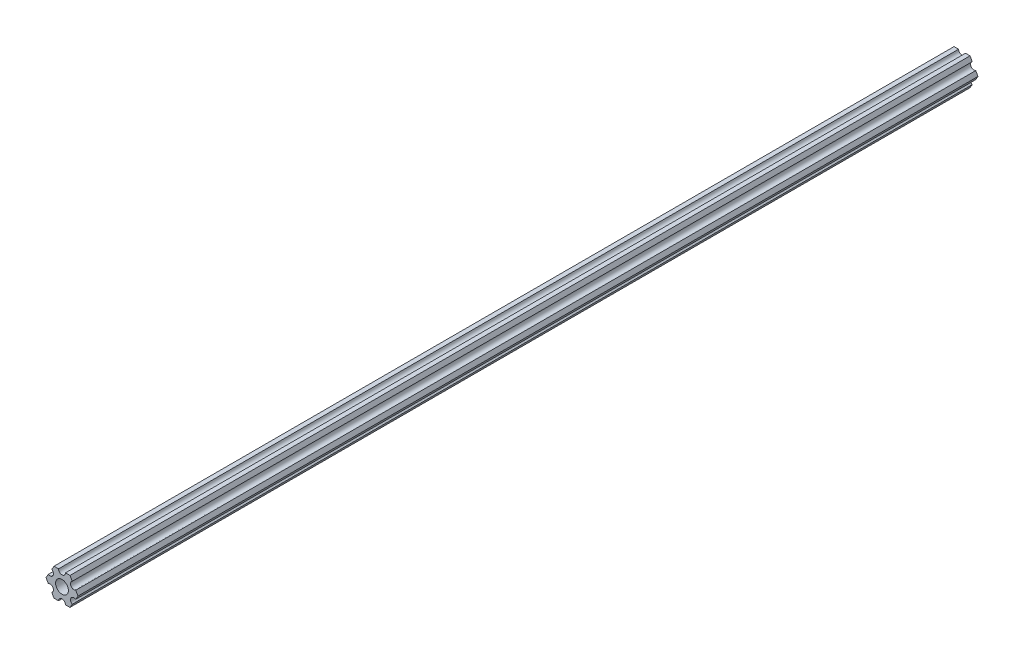
SolidWorks part; units mm, degrees
ref_plane "Front Plane" through (0, 0, 0) normal (0, 0, 1) x (1, 0, 0)
ref_plane "Top Plane" through (0, 0, 0) normal (0, 1, 0) x (1, 0, 0)
ref_plane "Right Plane" through (0, 0, 0) normal (1, 0, 0) x (0, 0, -1)
sketch "Sketch1" plane through (0, 0, 0) normal (0, 0, 1) x (1, 0, 0)
  line L0 (-1.5875, 6.35) -> (-3.6662, 6.35)
  line L1 (7.3323, 0) -> (6.293, 1.8002)
  line L2 (3.6662, 6.35) -> (1.5875, 6.35)
  line L3 (-3.6662, 6.35) -> (-4.7055, 4.5498)
  line L4 (-7.3323, 0) -> (-6.293, -1.8002)
  line L5 (-3.6662, -6.35) -> (-1.5875, -6.35)
  line L6 (3.6662, -6.35) -> (4.7055, -4.5498)
  line L7 (-6.293, 1.8002) -> (-7.3323, 0)
  line L8 (-4.7055, -4.5498) -> (-3.6662, -6.35)
  line L9 (1.5875, -6.35) -> (3.6662, -6.35)
  line L10 (6.293, -1.8002) -> (7.3323, 0)
  line L11 (4.7055, 4.5498) -> (3.6662, 6.35)
  circle A0 centre (0, 0) radius 2.9337
  arc A2 (-1.5875, 6.35) -> (1.5875, 6.35) centre (0, 6.35) ccw
  arc A3 (4.7055, 4.5498) -> (6.293, 1.8002) centre (5.4993, 3.175) ccw
  arc A4 (6.293, -1.8002) -> (4.7055, -4.5498) centre (5.4993, -3.175) ccw
  arc A5 (1.5875, -6.35) -> (-1.5875, -6.35) centre (0, -6.35) ccw
  arc A6 (-4.7055, -4.5498) -> (-6.293, -1.8002) centre (-5.4993, -3.175) ccw
  arc A7 (-6.293, 1.8002) -> (-4.7055, 4.5498) centre (-5.4993, 3.175) ccw
  dimension "D1" = 5.8674
  dimension "D3" = 3.175
  dimension "D4" = 6
extrude "Boss-Extrude1" add sketch "Sketch1" along normal blind 412.75
